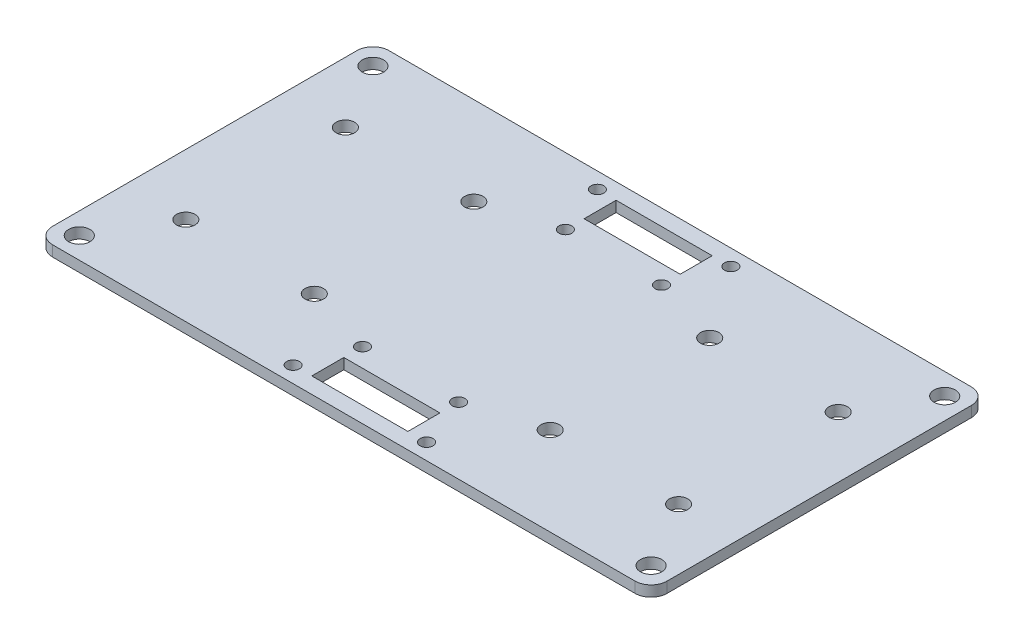
SolidWorks part; units mm, degrees
ref_plane "Plano frontal" through (0, 0, 0) normal (0, 0, 1) x (1, 0, 0)
ref_plane "Plano superior" through (0, 0, 0) normal (0, 1, 0) x (1, 0, 0)
ref_plane "Plano direito" through (0, 0, 0) normal (1, 0, 0) x (0, 0, -1)
sketch "Esboço1" plane through (0, 0, 0) normal (0, 1, 0) x (1, 0, 0)
  line L7 (-57.5484, 31.5) -> (57.5484, 31.5)
  line L8 (57.5484, 31.5) -> (57.5484, -31.5)
  line L9 (57.5484, -31.5) -> (-57.5484, -31.5)
  line L10 (-57.5484, -31.5) -> (-57.5484, 31.5)
  line L11 (0, 31.5) -> (0, -31.5) construction
  line L12 (-57.5484, 0) -> (57.5484, 0) construction
  dimension "D1" = 63
  dimension "D2" = 115.0968
extrude "Ressalto-extrusão1" add sketch "Esboço1" along normal blind 2
sketch "Esboço2" plane through (0, 2, 0) normal (0, 1, 0) x (1, 0, 0)
  line L0 (-57.5484, 0) -> (57.5484, 0) construction
  line L1 (-57.5484, 31.5) -> (-57.5484, -31.5) construction
  line L2 (-57.5484, -31.5) -> (57.5484, -31.5) construction
  line L5 (57.5484, -31.5) -> (57.5484, 31.5) construction
  line L6 (0, -31.5) -> (0, 31.5) construction
  line L7 (57.5484, 31.5) -> (-57.5484, 31.5) construction
  circle A8 centre (-46.1536, -14.945) radius 1.73
  circle A10 centre (-22.0936, -14.94) radius 1.73
  circle A11 centre (22.0936, -14.94) radius 1.73
  circle A12 centre (46.1536, -14.945) radius 1.73
  circle A13 centre (46.1536, 14.945) radius 1.73
  circle A14 centre (22.0936, 14.94) radius 1.73
  circle A15 centre (-22.0936, 14.94) radius 1.73
  circle A16 centre (-46.1536, 14.945) radius 1.73
  dimension "D1" = 16.555
  dimension "D3" = 3.46
  dimension "D4" = 24.06
  dimension "D2" = 11.3948
  dimension "D5" = 16.56
extrude "Corte-extrusão1" cut sketch "Esboço2" against normal through all
sketch "Esboço3" plane through (0, 0, 0) normal (0, -1, 0) x (1, 0, 0)
  line L0 (0, 31.5) -> (0, 28.5) construction
  line L1 (-57.5484, 31.5) -> (57.5484, 31.5) construction
  line L2 (-9, 28.5) -> (9, 28.5)
  line L3 (9, 28.5) -> (9, 22.5)
  line L4 (-9, 28.5) -> (-9, 22.5)
  line L5 (-9, 22.5) -> (9, 22.5)
  line L6 (-57.5484, 0) -> (57.5484, 0) construction
  line L7 (-57.5484, -31.5) -> (-57.5484, 31.5) construction
  line L8 (57.5484, 31.5) -> (57.5484, -31.5) construction
  line L9 (9, 28.5) -> (9, 22.5)
  line L10 (-9, 28.5) -> (-9, 22.5)
  line L11 (9, 28.5) -> (9, 22.5)
  line L12 (-9, 28.5) -> (-9, 22.5)
  line L13 (9, 28.5) -> (9, 22.5)
  line L14 (-9, 28.5) -> (-9, 22.5)
  line L15 (0, -31.5) -> (0, -28.5) construction
  line L16 (-9, -28.5) -> (-9, -22.5)
  line L17 (9, -28.5) -> (9, -22.5)
  line L18 (-9, -28.5) -> (-9, -22.5)
  line L19 (9, -28.5) -> (9, -22.5)
  line L20 (-9, -28.5) -> (-9, -22.5)
  line L21 (9, -28.5) -> (9, -22.5)
  line L22 (-9, -22.5) -> (9, -22.5)
  line L23 (-9, -28.5) -> (-9, -22.5)
  line L24 (9, -28.5) -> (9, -22.5)
  line L25 (-9, -28.5) -> (9, -28.5)
  point P8 (0, 28.5)
  point P22 (0, -28.5)
  dimension "D1" = 3
  dimension "D2" = 18
  dimension "D3" = 6
extrude "Corte-extrusão2" cut sketch "Esboço3" against normal through all contours L4 L5 L3 L2 | L16 L25 L17 L22
sketch "Esboço5" plane through (0, 2, 0) normal (0, 1, 0) x (1, 0, 0)
  line L2 (57.5484, 31.5) -> (-57.5484, 31.5) construction
  line L3 (57.5484, -31.5) -> (57.5484, 31.5) construction
  line L4 (57.5484, 0) -> (-57.5484, 0) construction
  line L5 (-57.5484, 31.5) -> (-57.5484, -31.5) construction
  line L6 (0, 31.5) -> (0, -31.5) construction
  line L7 (-57.5484, -31.5) -> (57.5484, -31.5) construction
  line L8 (53.5484, -13.175) -> (53.5484, -27.5) construction
  line L9 (-53.5484, -13.175) -> (-53.5484, -27.5) construction
  line L10 (-53.5484, 21.175) -> (-53.5484, 35.5) construction
  circle A0 centre (53.5484, 27.5) radius 2
  circle A1 centre (53.5484, -27.5) radius 2
  circle A2 centre (-53.5484, -27.5) radius 2
  circle A3 centre (-53.5484, 27.5) radius 2
  dimension "D2" = 4
  dimension "D1" = 4
  dimension "D3" = 4
extrude "Corte-extrusão3" cut sketch "Esboço5" against normal through all
fillet "Filete1" radius 3 4 edges at (57.5484, 1, -31.5) (57.5484, 1, 31.5) (-57.5484, 1, 31.5) (-57.5484, 1, -31.5)
sketch "Esboço8" plane through (0, 2, 0) normal (0, 1, 0) x (1, 0, 0)
  line L0 (-57.5484, 28.5) -> (-57.5484, -28.5) construction
  line L1 (54.5484, 31.5) -> (-54.5484, 31.5) construction
  line L2 (0, 0) -> (0, 31.5) construction
  line L3 (57.5484, 0) -> (-57.5484, 0) construction
  line L4 (-54.5484, -31.5) -> (54.5484, -31.5) construction
  line L5 (57.5484, -28.5) -> (57.5484, 28.5) construction
  circle A0 centre (-12.4984, 28.5) radius 1.2
  circle A1 centre (12.4984, 28.5) radius 1.2
  circle A2 centre (12.4984, -28.5) radius 1.2
  circle A3 centre (-12.4984, -28.5) radius 1.2
  circle A8 centre (-8.9984, -19) radius 1.2
  circle A12 centre (8.9984, -19) radius 1.2
  circle A13 centre (8.9984, 19) radius 1.2
  circle A14 centre (-8.9984, 19) radius 1.2
  dimension "D1" = 2.4
  dimension "D4" = 2.4
  dimension "D5" = 12.5
  dimension "D6" = 48.55
  dimension "D2" = 45.05
  dimension "D3" = 3
extrude "Corte-extrusão4" cut sketch "Esboço8" against normal through all
